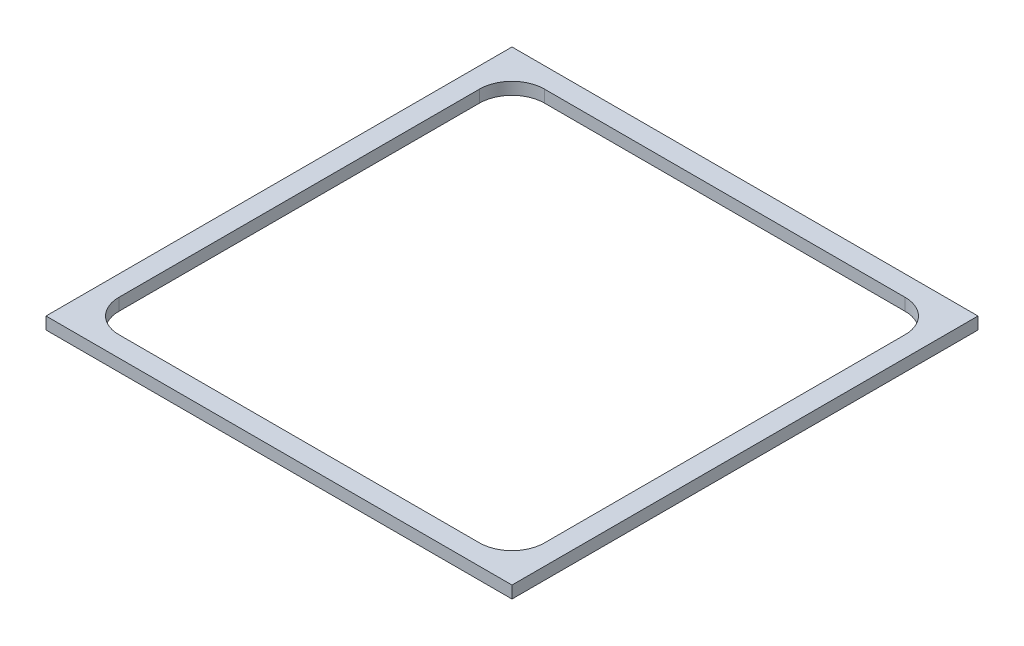
SolidWorks part; units mm, degrees
material "Резина"
ref_plane "Спереди" through (0, 0, 0) normal (0, 0, 1) x (1, 0, 0)
ref_plane "Сверху" through (0, 0, 0) normal (0, 1, 0) x (1, 0, 0)
ref_plane "Справа" through (0, 0, 0) normal (1, 0, 0) x (0, 0, -1)
sketch "Эскиз1" plane through (0, 0, 0) normal (0, 1, 0) x (1, 0, 0)
  line L0 (-57.5, -57.5) -> (57.5, -57.5)
  line L1 (-57.5, -57.5) -> (-57.5, 57.5)
  line L2 (-57.5, 57.5) -> (57.5, 57.5)
  line L3 (57.5, -57.5) -> (57.5, 57.5)
  line L4 (-57.5, 0) -> (57.5, 0) construction
  line L5 (-44.5, -52.5) -> (44.5, -52.5)
  line L6 (-52.5, -44.5) -> (-52.5, 44.5)
  line L7 (-44.5, 52.5) -> (44.5, 52.5)
  line L8 (52.5, -44.5) -> (52.5, 44.5)
  line L9 (0, 0) -> (0, -54.0653) construction
  arc A0 (-52.5, 44.5) -> (-44.5, 52.5) centre (-44.5, 44.5) cw
  arc A1 (44.5, 52.5) -> (52.5, 44.5) centre (44.5, 44.5) cw
  arc A2 (52.5, -44.5) -> (44.5, -52.5) centre (44.5, -44.5) cw
  arc A3 (-52.5, -44.5) -> (-44.5, -52.5) centre (-44.5, -44.5) ccw
  dimension "D6" = 8
  dimension "D1" = 115
  dimension "D2" = 5
  dimension "D3" = 5
  dimension "D4" = 5
  dimension "D5" = 5
  dimension "D7" = 115
extrude "Бобышка-Вытянуть1" add sketch "Эскиз1" along normal blind 3
